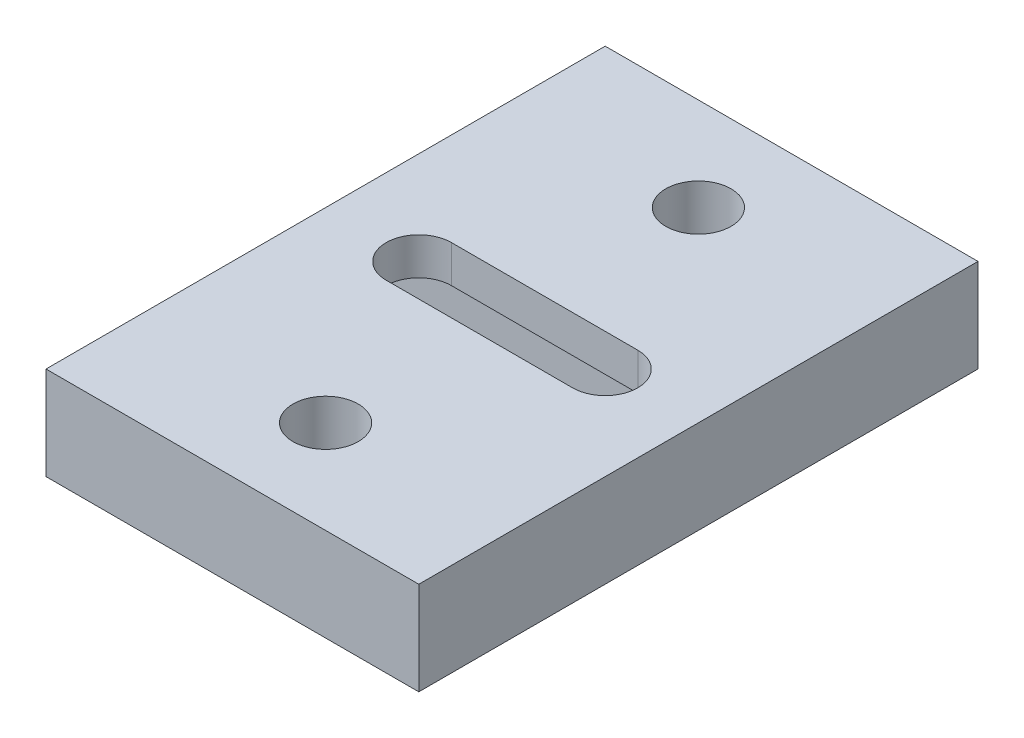
SolidWorks part; units mm, degrees
material "ABS"
ref_plane "Front Plane" through (0, 0, 0) normal (0, 0, 1) x (1, 0, 0)
ref_plane "Top Plane" through (0, 0, 0) normal (0, 1, 0) x (1, 0, 0)
ref_plane "Right Plane" through (0, 0, 0) normal (1, 0, 0) x (0, 0, -1)
sketch "Sketch1" plane through (0, 0, 0) normal (0, 1, 0) x (1, 0, 0)
  line L1 (0, 0) -> (20, 0)
  line L2 (0, 0) -> (0, 30)
  line L3 (0, 30) -> (20, 30)
  line L4 (20, 0) -> (20, 30)
  dimension "D1" = 20
  dimension "D2" = 30
extrude "Boss-Extrude1" add sketch "Sketch1" along normal blind 5
sketch "Sketch2" plane through (0, 5, 0) normal (0, 1, 0) x (1, 0, 0)
  line L2 (5, 16.75) -> (15, 16.75)
  line L3 (5, 13.25) -> (15, 13.25)
  line L4 (0, 30) -> (0, 0) construction
  arc A1 (15, 16.75) -> (15, 13.25) centre (15, 15) cw
  arc A2 (5, 13.25) -> (5, 16.75) centre (5, 15) cw
  dimension "D1" = 1.75
  dimension "D2" = 5
  dimension "D3" = 15
  dimension "D4" = 10
extrude "Cut-Extrude1" cut sketch "Sketch2" against normal blind 8
sketch "Sketch3" plane through (0, 5, 0) normal (0, 1, 0) x (1, 0, 0)
  line L0 (20, 30) -> (0, 30) construction
  line L1 (0, 30) -> (0, 0) construction
  line L2 (0, 0) -> (20, 0) construction
  circle A0 centre (10, 25) radius 1.75
  circle A1 centre (10, 5) radius 1.75
  dimension "D1" = 3.5
  dimension "D4" = 3.5
  dimension "D2" = 5
  dimension "D3" = 10
  dimension "D5" = 5
extrude "Cut-Extrude2" cut sketch "Sketch3" against normal through all
sketch "Sketch4" plane through (0, 0, 0) normal (-1, 0, 0) x (0, 0, 1)
  line L1 (-18, 0) -> (-12.3, 0)
  line L2 (-18, 0) -> (-18, 3)
  line L3 (-18, 3) -> (-12.3, 3)
  line L4 (-12.3, 0) -> (-12.3, 3)
  line L5 (-30, 5) -> (-30, 0) construction
  dimension "D1" = 3
  dimension "D2" = 5.7
  dimension "D3" = 12
extrude "Cut-Extrude3" cut sketch "Sketch4" against normal blind 18
